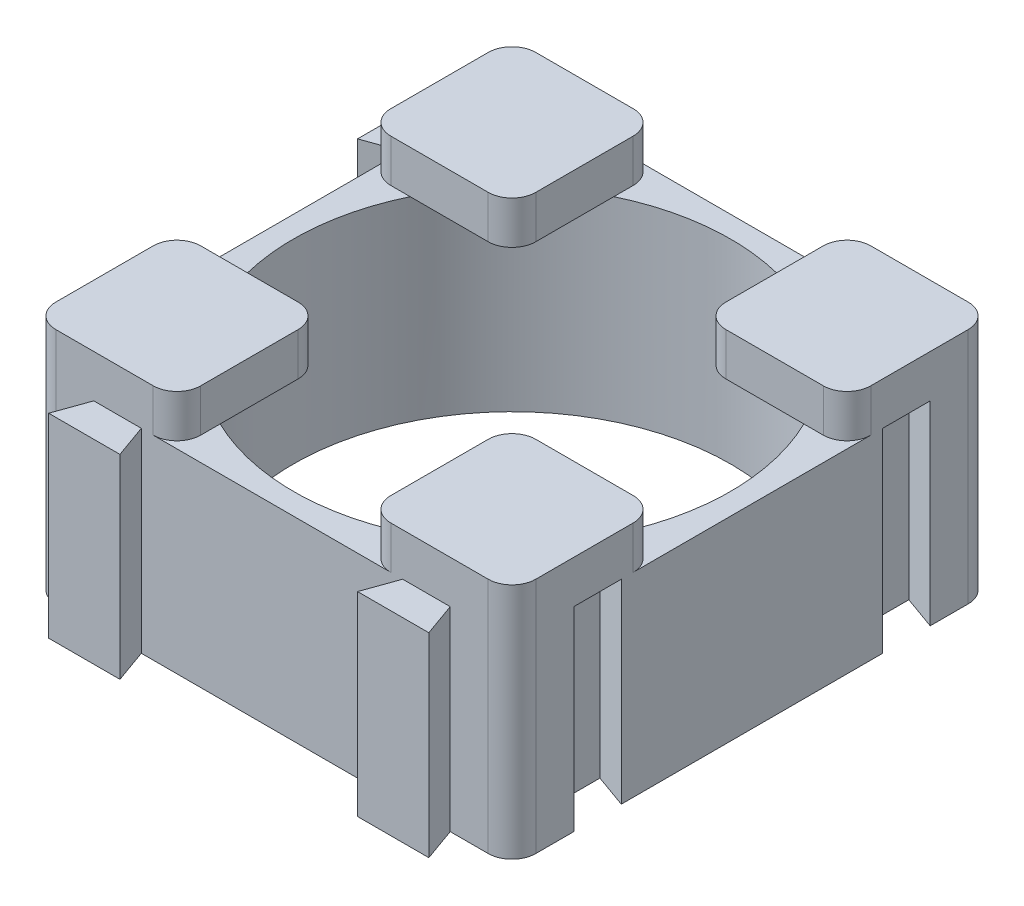
SolidWorks part; units mm, degrees
material "ABS"
ref_plane "Front Plane" through (0, 0, 0) normal (0, 0, 1) x (1, 0, 0)
ref_plane "Top Plane" through (0, 0, 0) normal (0, 1, 0) x (1, 0, 0)
ref_plane "Right Plane" through (0, 0, 0) normal (1, 0, 0) x (0, 0, -1)
sketch "Sketch1" plane through (0, 0, 0) normal (0, 1, 0) x (1, 0, 0)
  line L0 (-14.0032, 0) -> (15.5031, 0) construction
  line L1 (-9.1, 10.1) -> (-7.5, 10.1)
  line L2 (-10.1, 9.1) -> (-10.1, 7.5)
  line L3 (-9.1, -10.1) -> (-7.5, -10.1)
  line L4 (10.1, 9.1) -> (10.1, 7.5)
  line L5 (0, 12.8597) -> (0, -11.7289) construction
  line L6 (-10.1, 7.5) -> (-11.5, 8)
  line L7 (-11.5, 8) -> (-11.5, 5)
  line L8 (-11.5, 5) -> (-10.1, 5.5)
  line L9 (10.1, 7.5) -> (8.7, 8)
  line L10 (8.7, 8) -> (8.7, 5)
  line L11 (8.7, 5) -> (10.1, 5.5)
  line L12 (-10.1, 5.5) -> (-10.1, -5.5)
  line L13 (10.1, 5.5) -> (10.1, -5.5)
  line L14 (7.5, 10.1) -> (8, 8.7)
  line L15 (8, 8.7) -> (5, 8.7)
  line L16 (5, 8.7) -> (5.5, 10.1)
  line L17 (7.5, 10.1) -> (9.1, 10.1)
  line L18 (-7.5, -10.1) -> (-8, -11.5)
  line L19 (-8, -11.5) -> (-5, -11.5)
  line L20 (-5, -11.5) -> (-5.5, -10.1)
  line L21 (-5.5, -10.1) -> (5.5, -10.1)
  line L22 (-11.5, -5) -> (-10.1, -5.5)
  line L23 (-11.5, -8) -> (-11.5, -5)
  line L24 (-10.1, -7.5) -> (-11.5, -8)
  line L25 (-10.1, -7.5) -> (-10.1, -9.1)
  line L26 (5, -11.5) -> (5.5, -10.1)
  line L27 (8, -11.5) -> (5, -11.5)
  line L28 (7.5, -10.1) -> (8, -11.5)
  line L29 (7.5, -10.1) -> (9.1, -10.1)
  line L30 (-5, 8.7) -> (-5.5, 10.1)
  line L31 (-8, 8.7) -> (-5, 8.7)
  line L32 (-7.5, 10.1) -> (-8, 8.7)
  line L33 (-5.5, 10.1) -> (5.5, 10.1)
  line L34 (8.7, -5) -> (10.1, -5.5)
  line L35 (8.7, -8) -> (8.7, -5)
  line L36 (10.1, -7.5) -> (8.7, -8)
  line L37 (10.1, -7.5) -> (10.1, -9.1)
  arc A0 (-10.1, -9.1) -> (-9.1, -10.1) centre (-9.1, -9.1) ccw
  arc A1 (9.1, -10.1) -> (10.1, -9.1) centre (9.1, -9.1) ccw
  arc A2 (9.1, 10.1) -> (10.1, 9.1) centre (9.1, 9.1) cw
  arc A3 (-9.1, 10.1) -> (-10.1, 9.1) centre (-9.1, 9.1) ccw
  circle A4 centre (0, 0) radius 9.2
  point P7 (-10.1, -10.1)
  point P10 (10.1, -10.1)
  point P13 (10.1, 10.1)
  point P54 (-6.5, -11.5)
  point P55 (6.5, -11.5)
  dimension "D5" = 1
  dimension "D6" = 18.4
  dimension "D1" = 20.2
  dimension "D2" = 20.2
  dimension "D3" = 10.1
  dimension "D4" = 10.1
  dimension "D7" = 1.4
  dimension "D8" = 1.4
  dimension "D9" = 3
  dimension "D10" = 3
  dimension "D11" = 2
  dimension "D12" = 0.5
  dimension "D13" = 5
  dimension "D14" = 2
  dimension "D15" = 3
  dimension "D16" = 0.5
  dimension "D17" = 5
  dimension "D18" = 1.4
  dimension "D19" = 3
  dimension "D20" = 2
  dimension "D21" = 0.5
  dimension "D22" = 1.4
  dimension "D23" = 13
extrude "Boss-Extrude1" add sketch "Sketch1" along normal blind 8.2
sketch "Sketch2" plane through (0, 8.2, 0) normal (0, 1, 0) x (1, 0, 0)
  line L0 (-9.1, 4) -> (-5, 4)
  line L1 (-10.1, 5.5) -> (-10.1, -5.5) construction
  line L2 (-4, 5) -> (-4, 9.1)
  line L3 (5.5, 10.1) -> (-5.5, 10.1) construction
  line L4 (-5, 10.1) -> (-9.1, 10.1)
  line L5 (-10.1, 9.1) -> (-10.1, 5)
  line L6 (0, 2.2334) -> (0, -2.7823) construction
  line L7 (-2.0812, 0) -> (2.2435, 0) construction
  line L8 (10.1, 9.1) -> (10.1, 5)
  line L9 (5, 10.1) -> (9.1, 10.1)
  line L10 (4, 5) -> (4, 9.1)
  line L11 (9.1, 4) -> (5, 4)
  line L12 (9.1, -4) -> (5, -4)
  line L13 (10.1, -9.1) -> (10.1, -5)
  line L14 (5, -10.1) -> (9.1, -10.1)
  line L15 (4, -5) -> (4, -9.1)
  line L16 (-4, -5) -> (-4, -9.1)
  line L17 (-5, -10.1) -> (-9.1, -10.1)
  line L18 (-10.1, -9.1) -> (-10.1, -5)
  line L19 (-9.1, -4) -> (-5, -4)
  arc A0 (-4, 9.1) -> (-5, 10.1) centre (-5, 9.1) ccw
  arc A1 (-5, 4) -> (-4, 5) centre (-5, 5) ccw
  arc A2 (-9.1, 4) -> (-10.1, 5) centre (-9.1, 5) cw
  arc A3 (-9.1, 10.1) -> (-10.1, 9.1) centre (-9.1, 9.1) ccw
  arc A4 (9.1, 10.1) -> (10.1, 9.1) centre (9.1, 9.1) cw
  arc A5 (4, 9.1) -> (5, 10.1) centre (5, 9.1) cw
  arc A6 (5, 4) -> (4, 5) centre (5, 5) cw
  arc A7 (9.1, 4) -> (10.1, 5) centre (9.1, 5) ccw
  arc A8 (5, -4) -> (4, -5) centre (5, -5) ccw
  arc A9 (9.1, -4) -> (10.1, -5) centre (9.1, -5) cw
  arc A10 (9.1, -10.1) -> (10.1, -9.1) centre (9.1, -9.1) ccw
  arc A11 (4, -9.1) -> (5, -10.1) centre (5, -9.1) ccw
  arc A12 (-5, -4) -> (-4, -5) centre (-5, -5) cw
  arc A13 (-4, -9.1) -> (-5, -10.1) centre (-5, -9.1) cw
  arc A14 (-9.1, -10.1) -> (-10.1, -9.1) centre (-9.1, -9.1) cw
  arc A15 (-9.1, -4) -> (-10.1, -5) centre (-9.1, -5) ccw
  point P10 (-4, 10.1)
  point P13 (-4, 4)
  point P16 (-10.1, 4)
  dimension "D3" = 1
  dimension "D1" = 6.1
  dimension "D2" = 6.1
extrude "Boss-Extrude2" add sketch "Sketch2" along normal blind 1.8
